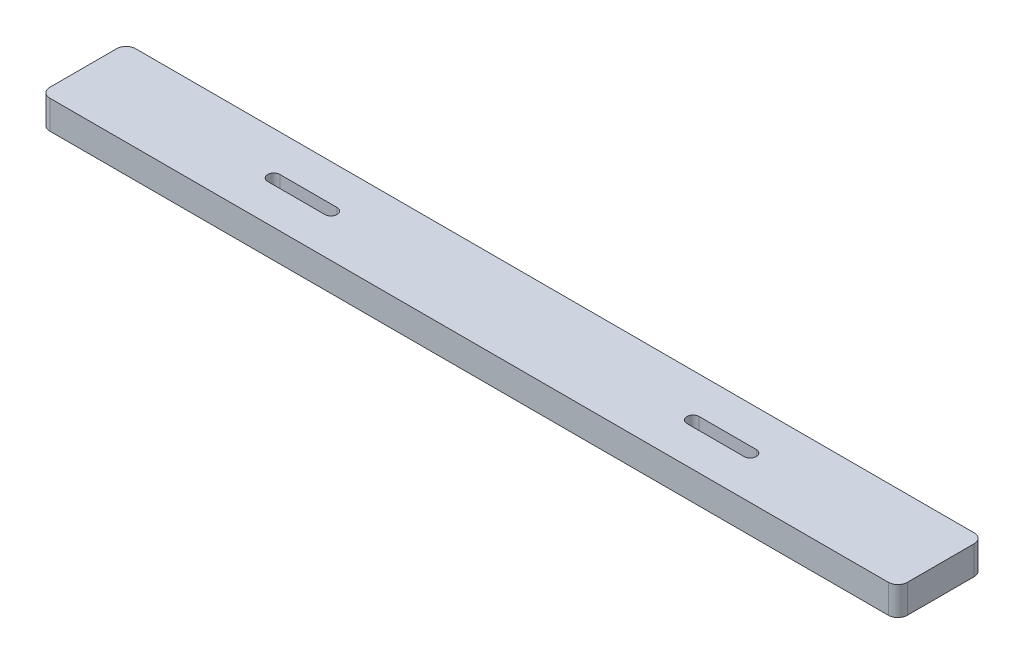
SolidWorks part; units mm, degrees
ref_plane "Front" through (0, 0, 0) normal (0, 0, 1) x (1, 0, 0)
ref_plane "Top" through (0, 0, 0) normal (0, 1, 0) x (1, 0, 0)
ref_plane "Right" through (0, 0, 0) normal (1, 0, 0) x (0, 0, -1)
sketch "Sketch1" plane through (0, 0, 0) normal (0, 1, 0) x (1, 0, 0)
  line L1 (285.75, -28.575) -> (-285.75, -28.575)
  line L2 (285.75, -28.575) -> (285.75, 28.575)
  line L3 (285.75, 28.575) -> (-285.75, 28.575)
  line L4 (-285.75, -28.575) -> (-285.75, 28.575)
  line L5 (285.75, -28.575) -> (-285.75, 28.575) construction
  line L6 (285.75, 28.575) -> (-285.75, -28.575) construction
  point P0 (0, 0)
  dimension "D1" = 57.15
  dimension "D2" = 571.5
extrude "Boss-Extrude1" add sketch "Sketch1" along normal blind 19.05
fillet "Fillet1" radius 6.35 4 edges at (-285.75, 9.525, -28.575) (285.75, 9.525, -28.575) (285.75, 9.525, 28.575) (-285.75, 9.525, 28.575)
sketch "Sketch2" plane through (0, 19.05, 0) normal (0, 1, 0) x (1, 0, 0)
  line L0 (0, 0) -> (-120.65, 0) construction
  line L1 (0, 0) -> (0, 28.575) construction
  line L3 (-120.65, 0) -> (-158.75, 0) construction
  line L4 (-120.65, -4.064) -> (-158.75, -4.064)
  line L5 (-120.65, 4.064) -> (-158.75, 4.064)
  line L6 (120.65, 0) -> (158.75, 0) construction
  line L7 (120.65, -4.064) -> (158.75, -4.064)
  line L8 (120.65, 4.064) -> (158.75, 4.064)
  line L9 (279.4, 28.575) -> (-279.4, 28.575) construction
  arc A0 (-120.65, -4.064) -> (-120.65, 4.064) centre (-120.65, 0) ccw
  arc A1 (-158.75, 4.064) -> (-158.75, -4.064) centre (-158.75, 0) ccw
  arc A2 (120.65, -4.064) -> (120.65, 4.064) centre (120.65, 0) cw
  arc A3 (158.75, 4.064) -> (158.75, -4.064) centre (158.75, 0) cw
  point P2 (-139.7, 0)
  point P15 (139.7, 0)
  dimension "D1" = 8.128
  dimension "D2" = 38.1
  dimension "D3" = 120.65
extrude "Cut-Extrude1" cut sketch "Sketch2" against normal blind 19.05
